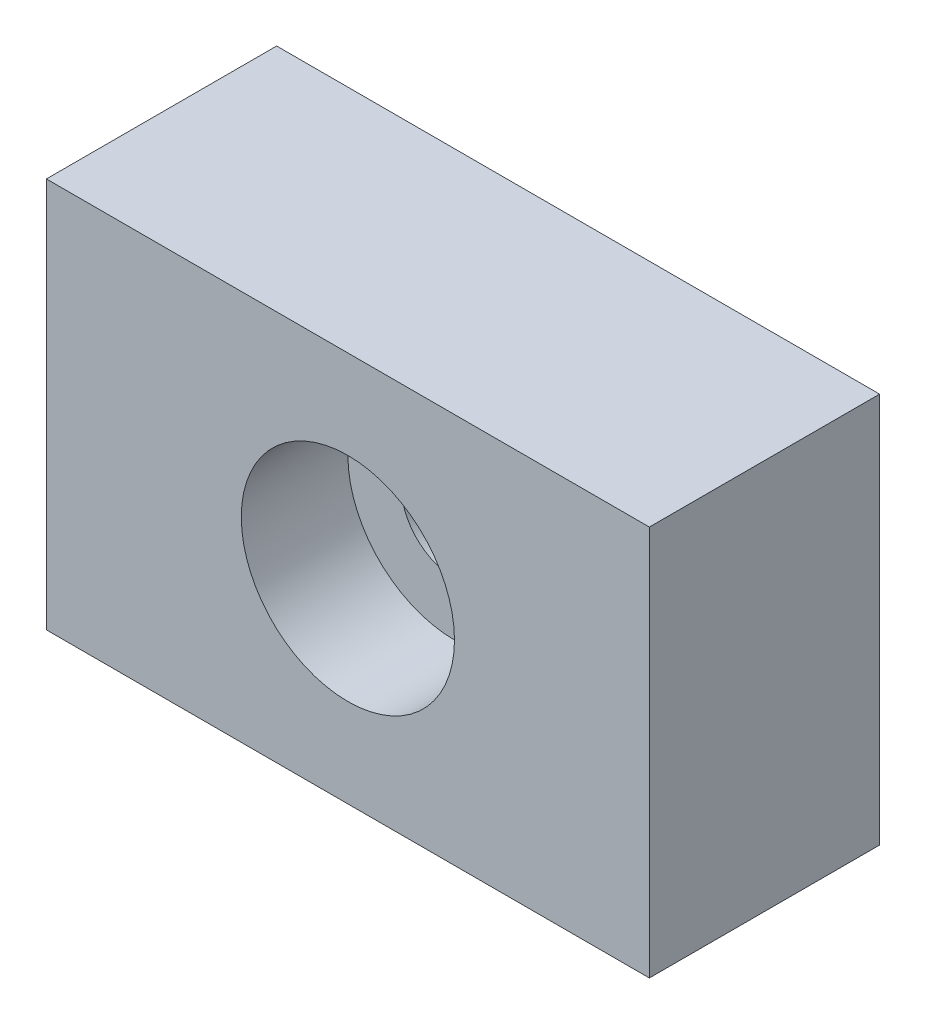
SolidWorks part; units mm, degrees
ref_plane "Front Plane" through (0, 0, 0) normal (0, 0, 1) x (1, 0, 0)
ref_plane "Top Plane" through (0, 0, 0) normal (0, 1, 0) x (1, 0, 0)
ref_plane "Right Plane" through (0, 0, 0) normal (1, 0, 0) x (0, 0, -1)
sketch "Sketch1" plane through (0, 0, 0) normal (0, 0, 1) x (1, 0, 0)
  line L1 (-7.0711, 4.5801) -> (7.0711, 4.5801)
  line L2 (-7.0711, 4.5801) -> (-7.0711, -4.5801)
  line L3 (-7.0711, -4.5801) -> (7.0711, -4.5801)
  line L4 (7.0711, 4.5801) -> (7.0711, -4.5801)
  line L5 (-7.0711, 4.5801) -> (7.0711, -4.5801) construction
  line L6 (-7.0711, -4.5801) -> (7.0711, 4.5801) construction
  circle A0 centre (0, 0) radius 1.25
  point P0 (0, 0)
  dimension "D1" = 2.5
extrude "Boss-Extrude1" add sketch "Sketch1" along normal blind 5.4
sketch "Sketch2" plane through (0, 0, 5.4) normal (0, 0, 1) x (1, 0, 0)
  circle A0 centre (0, 0) radius 2.5
  dimension "D1" = 5
extrude "Cut-Extrude1" cut sketch "Sketch2" against normal blind 2.5
